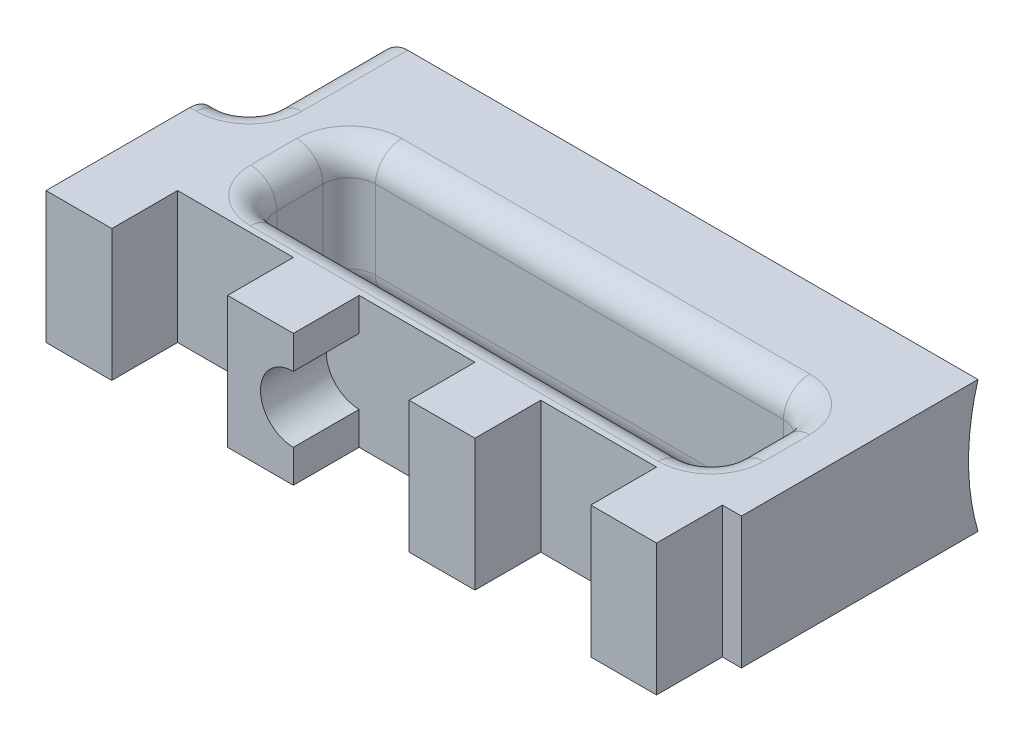
SolidWorks part; units mm, degrees
ref_plane "Front Plane" through (0, 0, 0) normal (0, 0, 1) x (1, 0, 0)
ref_plane "Top Plane" through (0, 0, 0) normal (0, 1, 0) x (1, 0, 0)
ref_plane "Right Plane" through (0, 0, 0) normal (1, 0, 0) x (0, 0, -1)
sketch "Sketch1" plane through (0, 0, 0) normal (0, 1, 0) x (1, 0, 0)
  line L0 (0, 22.225) -> (0, -22.225) construction
  line L1 (28.6599, -20.131) -> (26.8197, -20.131)
  line L2 (28.6599, -20.131) -> (28.6599, 17.969)
  line L3 (28.6599, 17.969) -> (-28.8983, 17.969)
  line L4 (-32.1083, 12.8512) -> (-32.1083, -20.131)
  line L5 (-28.8983, 12.8512) -> (-32.1083, 12.8512)
  line L6 (28.6599, 17.969) -> (-32.1083, -20.131) construction
  line L7 (22.6216, -17.0219) -> (-21.8284, -17.0219)
  line L8 (22.6216, -17.0219) -> (22.6216, -7.4969)
  line L9 (22.6216, -7.4969) -> (-21.8284, -7.4969)
  line L10 (-14.5823, -26.481) -> (-8.2323, -26.481)
  line L12 (-32.1083, -20.131) -> (-32.1083, -26.481)
  line L13 (-32.1083, -26.481) -> (-25.7583, -26.481)
  line L14 (-25.7583, -20.131) -> (-25.7583, -26.481)
  line L15 (-14.5823, -20.131) -> (-14.5823, -26.481)
  line L16 (-8.2323, -20.131) -> (-8.2323, -26.481)
  line L17 (2.9437, -26.481) -> (9.2937, -26.481)
  line L18 (2.9437, -20.131) -> (2.9437, -26.481)
  line L19 (9.2937, -20.131) -> (9.2937, -26.481)
  line L20 (20.4697, -26.481) -> (26.8197, -26.481)
  line L21 (20.4697, -20.131) -> (20.4697, -26.481)
  line L22 (26.8197, -20.131) -> (26.8197, -26.481)
  line L23 (-32.1083, -26.481) -> (-14.5823, -26.481) construction
  line L24 (-21.8284, -17.0219) -> (-21.8284, -7.4969)
  line L26 (-28.8983, 12.8512) -> (-28.8983, 17.969)
  line L27 (-14.5823, -20.131) -> (-25.7583, -20.131)
  line L28 (2.9437, -20.131) -> (-8.2323, -20.131)
  line L29 (20.4697, -20.131) -> (9.2937, -20.131)
  point P0 (0, 0)
  point P30 (0.3966, -7.4969)
  dimension "D4" = 6.35
  dimension "D5" = 6.35
  dimension "D6" = 0
  dimension "D8" = 17.526
  dimension "D3" = 44.45
  dimension "D9" = 9.525
  dimension "D7" = 4
extrude "Boss-Extrude1" add sketch "Sketch1" along normal blind 12.7
sketch "Sketch2" plane through (28.6599, 0, 0) normal (1, 0, 0) x (0, 0, -1)
  line L1 (-20.131, 12.7) -> (17.969, 12.7) construction
  line L2 (-20.131, 0) -> (17.969, 0) construction
  line L3 (2.7026, 12.7) -> (17.969, 12.7)
  line L4 (17.969, 12.7) -> (17.969, 0)
  line L6 (-20.131, 6.35) -> (24.319, 6.35) construction
  line L7 (-20.131, 12.7) -> (-20.131, 0) construction
  line L9 (17.969, 0) -> (2.7026, 0)
  arc A0 (2.7026, 12.7) -> (2.7026, 0) centre (24.319, 6.35) ccw
fillet "Fillet1" radius 2.54 4 edges at (22.6216, 6.35, 17.0219) (22.6216, 6.35, 7.4969) (-21.8284, 6.35, 7.4969) (-21.8284, 6.35, 17.0219)
fillet "Fillet2" radius 2.54 16 edges at (21.8777, 0, 16.278) (22.6216, 0, 12.2594) (21.8777, 0, 8.2409) (0.3966, 0, 7.4969) (-21.0844, 0, 8.2409) (-21.8284, 0, 12.2594) (-21.0844, 0, 16.278) (21.8777, 12.7, 8.2409) (22.6216, 12.7, 12.2594) (21.8777, 12.7, 16.278) (0.3966, 12.7, 17.0219) (-21.0844, 12.7, 16.278) (-21.8284, 12.7, 12.2594) (-21.0844, 12.7, 8.2409) (0.3966, 0, 17.0219) (0.3966, 12.7, 7.4969)
sketch "Sketch3" plane through (0, 0, 26.481) normal (0, 0, 1) x (1, 0, 0)
  line L0 (-8.2323, 12.7) -> (-8.2323, 0) construction
  line L1 (-8.2323, 12.7) -> (-8.2323, 0) construction
  line L2 (-8.2323, 9.525) -> (-8.2323, 3.175)
  arc A0 (-8.2323, 9.525) -> (-8.2323, 3.175) centre (-8.2323, 6.35) ccw
extrude "Cut-Extrude2" cut sketch "Sketch3" against normal up to surface (6.35 mm away) up to face at (-2.6443, 6.35, 20.131)
extrude "Cut-Extrude6" cut sketch "Sketch2" against normal through all
sketch "Sketch4" plane through (-32.1083, 0, 0) normal (-1, 0, 0) x (0, 0, 1)
  line L0 (26.481, 6.35) -> (-24.319, 6.35) construction
  line L1 (26.481, 12.7) -> (26.481, 0) construction
  line L2 (-2.7026, 12.7) -> (26.481, 12.7) construction
  line L3 (-2.7026, 0) -> (26.481, 0) construction
  line L4 (0.5367, 0) -> (-10.2407, 0)
  line L5 (-10.2407, 0) -> (-10.2407, 12.7)
  line L6 (-10.2407, 12.7) -> (0.5367, 12.7)
  arc A0 (0.5367, 12.7) -> (0.5367, 0) centre (-24.319, 6.35) cw
  dimension "D1" = 50.8
extrude "Cut-Extrude7" cut sketch "Sketch4" against normal blind 3.175
sketch "Sketch5" plane through (-32.1083, 0, 0) normal (-1, 0, 0) x (0, 0, 1)
  line L0 (0.5367, 0) -> (26.481, 0) construction
  line L1 (0.5367, 12.7) -> (10.0617, 12.7)
  line L2 (0.5367, 12.7) -> (0.5367, 0)
  line L3 (0.5367, 0) -> (10.0617, 0)
  line L4 (10.0617, 12.7) -> (10.0617, 0)
  dimension "D1" = 9.525
extrude "Cut-Extrude8" cut sketch "Sketch5" against normal blind 3.175
fillet "Fillet3" radius 2.54 5 edges at (-28.9333, 0, 3.6796) (-28.9333, 12.7, 3.6796) (-30.5208, 0, 10.0617) (-28.9333, 6.35, 10.0617) (-30.5208, 12.7, 10.0617)
